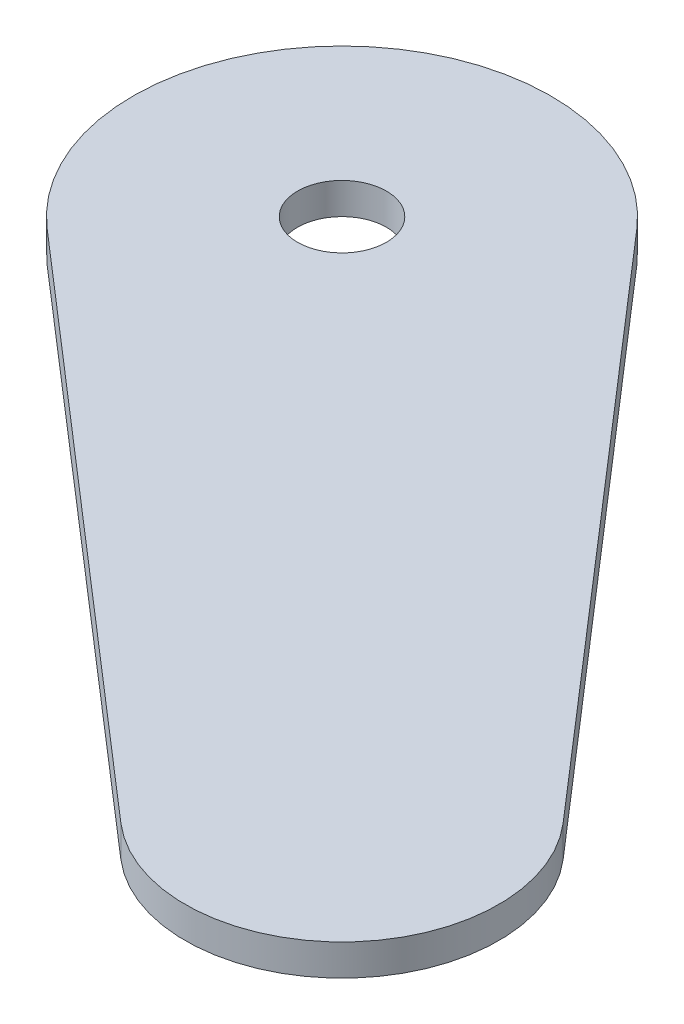
SolidWorks part; units mm, degrees
ref_plane "前视基准面" through (0, 0, 0) normal (0, 0, 1) x (1, 0, 0)
ref_plane "上视基准面" through (0, 0, 0) normal (0, 1, 0) x (1, 0, 0)
ref_plane "右视基准面" through (0, 0, 0) normal (1, 0, 0) x (0, 0, -1)
other "Configuration Table"
sketch "草图1" plane through (0, 0, 0) normal (0, 1, 0) x (1, 0, 0)
  line L0 (0, 0) -> (35.275, 0) construction
  line L1 (0, 0) -> (49.4975, -49.4975) construction
  line L2 (-13.0959, -15.1162) -> (39.6756, -60.8346)
  line L3 (15.1162, 13.0959) -> (60.8346, -39.6756)
  circle A0 centre (0, 0) radius 20
  circle A1 centre (49.4975, -49.4975) radius 15
  dimension "D1" = 40
  dimension "D3" = 30
  dimension "D2" = 70
extrude "凸台-拉伸1" add sketch "草图1" along normal blind 3 contours A0 | A1 L3 A0 L2 | A1
sketch "草图2" plane through (0, 3, 0) normal (0, 1, 0) x (1, 0, 0)
  circle A0 centre (0, 0) radius 2.5
  dimension "D1" = 5
extrude "切除-拉伸1" cut sketch "草图2" against normal through all
sketch "草图3" plane through (0, 3, 0) normal (0, 1, 0) x (1, 0, 0)
  circle A0 centre (0, 0) radius 5
  dimension "D1" = 10
extrude "切除-拉伸2" cut sketch "草图3" against normal blind 10
sketch "草图4" plane through (0, 3, 0) normal (0, 1, 0) x (1, 0, 0)
  circle A0 centre (0, 0) radius 4.25
  circle A1 centre (0, 0) radius 5
  dimension "D1" = 8.5
extrude "凸台-拉伸2" add sketch "草图4" against normal blind 3
